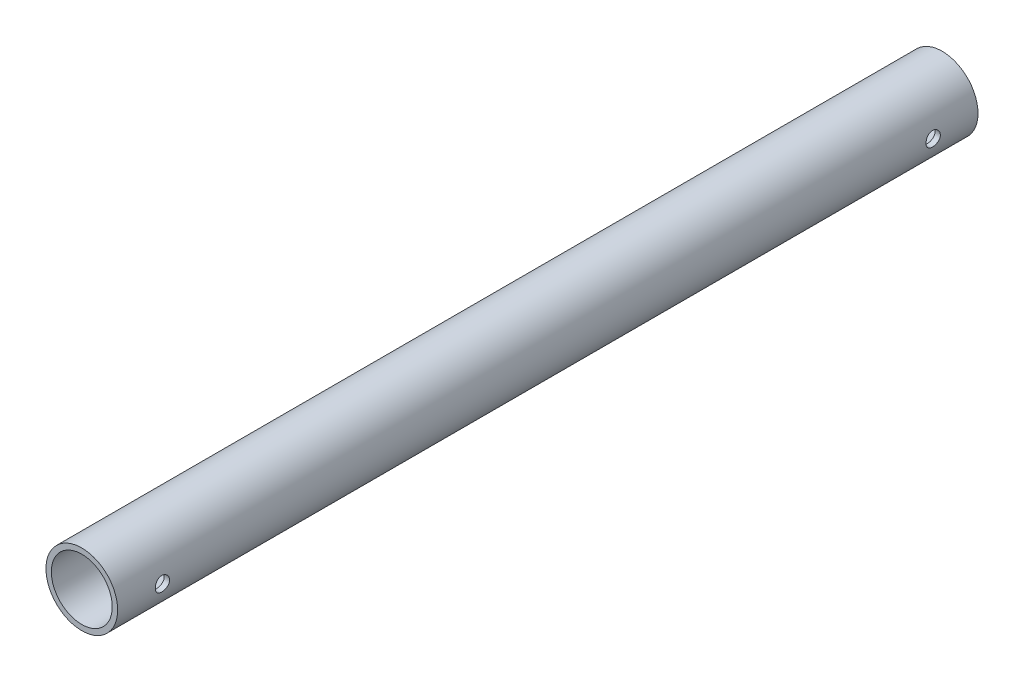
SolidWorks part; units mm, degrees
ref_plane "Front Plane" through (0, 0, 0) normal (0, 0, 1) x (1, 0, 0)
ref_plane "Top Plane" through (0, 0, 0) normal (0, 1, 0) x (1, 0, 0)
ref_plane "Right Plane" through (0, 0, 0) normal (1, 0, 0) x (0, 0, -1)
sketch "Sketch1" plane through (0, 0, 0) normal (0, 0, 1) x (1, 0, 0)
  circle A0 centre (0, 0) radius 8.5
  circle A1 centre (0, 0) radius 10
  dimension "D1" = 20
  dimension "D2" = 1.5
extrude "Boss-Extrude1" add sketch "Sketch1" along normal blind 120
sketch "Sketch2" plane through (0, 0, 0) normal (1, 0, 0) x (0, 0, -1)
  line L0 (-120, 10) -> (-120, -10) construction
  line L1 (0, 10) -> (-120, 10) construction
  circle A0 centre (-107.5, 0) radius 2
  point P4 (0, 0)
  dimension "D1" = 4
  dimension "D3" = 10
  dimension "D2" = 12.5
extrude "Cut-Extrude1" cut sketch "Sketch2" against normal through all both and the other way through all
mirror "Mirror1" about plane through (0, 0, 0) normal (0, 0, 1) of "Cut-Extrude1", "Boss-Extrude1"
